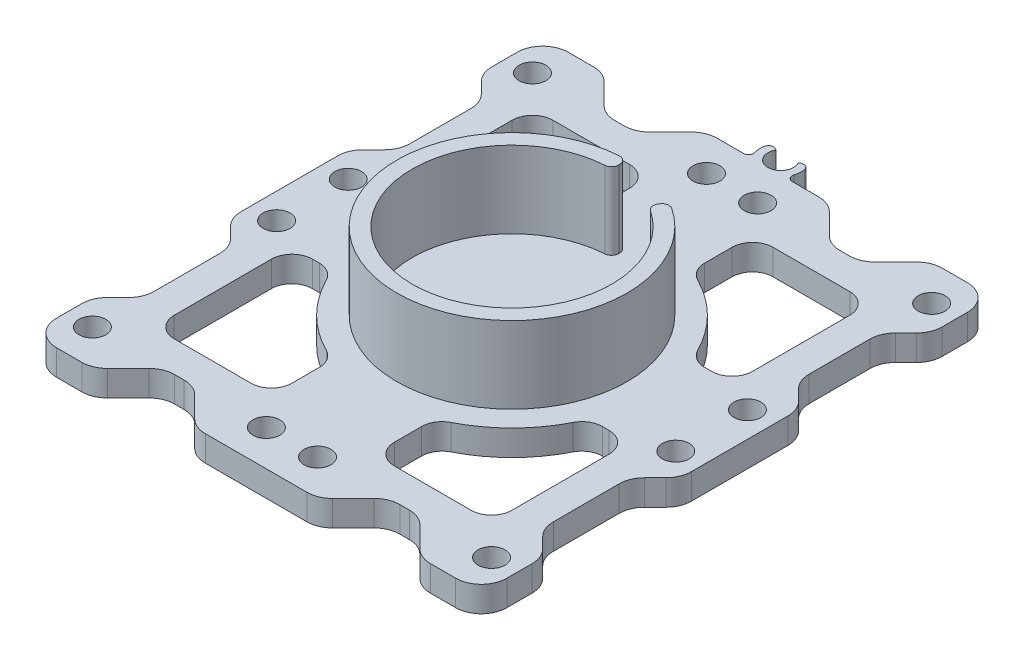
SolidWorks part; units mm, degrees
ref_plane "Front Plane" through (0, 0, 0) normal (0, 0, 1) x (1, 0, 0)
ref_plane "Top Plane" through (0, 0, 0) normal (0, 1, 0) x (1, 0, 0)
ref_plane "Right Plane" through (0, 0, 0) normal (1, 0, 0) x (0, 0, -1)
sketch "Sketch1" plane through (0, 0, 0) normal (0, 1, 0) x (1, 0, 0)
  line L1 (9.9289, 50) -> (4.7697, 50)
  line L2 (-44, 45) -> (-44, 40.0711)
  line L3 (-39, -50) -> (-34.0711, -50)
  line L5 (-30.5355, 48.5355) -> (-26.4645, 44.4645)
  line L6 (-22.9289, 43) -> (-21.0711, 43)
  line L7 (-17.5355, 44.4645) -> (-13.4645, 48.5355)
  line L8 (-42.5355, 36.5355) -> (-40.4645, 34.4645)
  line L9 (-39, 30.9289) -> (-39, 19.0711)
  line L10 (-40.4645, 15.5355) -> (-42.5355, 13.4645)
  line L11 (-42.5355, -12.4645) -> (-40.4645, -14.5355)
  line L12 (-39, -18.0711) -> (-39, -30.9289)
  line L13 (-40.4645, -34.4645) -> (-42.5355, -36.5355)
  line L14 (-30.5355, -48.5355) -> (-26.4645, -44.4645)
  line L15 (-22.9289, -43) -> (-21.0711, -43)
  line L16 (-17.5355, -44.4645) -> (-13.4645, -48.5355)
  line L17 (-34.0711, 50) -> (-39, 50)
  line L18 (-44, 9.9289) -> (-44, -8.9289)
  line L19 (-44, -40.0711) -> (-44, -45)
  line L20 (-9.9289, -50) -> (9.9289, -50)
  line L21 (0, -55) -> (0, 55) construction
  line L22 (44, -40.0711) -> (44, -45)
  line L23 (44, 9.9289) -> (44, -8.9289)
  line L24 (34.0711, 50) -> (39, 50)
  line L25 (17.5355, -44.4645) -> (13.4645, -48.5355)
  line L26 (22.9289, -43) -> (21.0711, -43)
  line L27 (30.5355, -48.5355) -> (26.4645, -44.4645)
  line L28 (40.4645, -34.4645) -> (42.5355, -36.5355)
  line L29 (39, -18.0711) -> (39, -30.9289)
  line L30 (42.5355, -12.4645) -> (40.4645, -14.5355)
  line L31 (40.4645, 15.5355) -> (42.5355, 13.4645)
  line L32 (39, 30.9289) -> (39, 19.0711)
  line L33 (42.5355, 36.5355) -> (40.4645, 34.4645)
  line L34 (17.5355, 44.4645) -> (13.4645, 48.5355)
  line L35 (22.9289, 43) -> (21.0711, 43)
  line L36 (30.5355, 48.5355) -> (26.4645, 44.4645)
  line L37 (39, -50) -> (34.0711, -50)
  line L38 (44, 45) -> (44, 40.0711)
  line L39 (-4.7697, 50) -> (-9.9289, 50)
  line L40 (2.1651, 53.75) -> (2.4495, 53.9142)
  line L42 (-2.1651, 53.75) -> (-2.4495, 53.9142)
  circle A0 centre (-39, 43) radius 2.625
  circle A1 centre (-5, 43) radius 2.625
  circle A2 centre (-39, 7) radius 2.625
  circle A3 centre (-39, -43) radius 2.625
  circle A4 centre (-5, -43) radius 2.625
  circle A5 centre (-39, -7) radius 2.625
  arc A6 (-13.4645, -48.5355) -> (-9.9289, -50) centre (-9.9289, -45) ccw
  arc A7 (-21.0711, -43) -> (-17.5355, -44.4645) centre (-21.0711, -48) cw
  arc A8 (-26.4645, -44.4645) -> (-22.9289, -43) centre (-22.9289, -48) cw
  arc A9 (-30.5355, -48.5355) -> (-34.0711, -50) centre (-34.0711, -45) cw
  arc A10 (-44, -45) -> (-39, -50) centre (-39, -45) ccw
  arc A11 (-42.5355, -36.5355) -> (-44, -40.0711) centre (-39, -40.0711) ccw
  arc A12 (-39, -30.9289) -> (-40.4645, -34.4645) centre (-44, -30.9289) cw
  arc A13 (-40.4645, -14.5355) -> (-39, -18.0711) centre (-44, -18.0711) cw
  arc A14 (-42.5355, -12.4645) -> (-44, -8.9289) centre (-39, -8.9289) cw
  arc A15 (-42.5355, 13.4645) -> (-44, 9.9289) centre (-39, 9.9289) ccw
  arc A16 (-39, 19.0711) -> (-40.4645, 15.5355) centre (-44, 19.0711) cw
  arc A17 (-40.4645, 34.4645) -> (-39, 30.9289) centre (-44, 30.9289) cw
  arc A18 (-42.5355, 36.5355) -> (-44, 40.0711) centre (-39, 40.0711) cw
  arc A19 (-13.4645, 48.5355) -> (-9.9289, 50) centre (-9.9289, 45) cw
  arc A20 (-21.0711, 43) -> (-17.5355, 44.4645) centre (-21.0711, 48) ccw
  arc A21 (-26.4645, 44.4645) -> (-22.9289, 43) centre (-22.9289, 48) ccw
  arc A22 (-30.5355, 48.5355) -> (-34.0711, 50) centre (-34.0711, 45) ccw
  arc A23 (-39, 50) -> (-44, 45) centre (-39, 45) ccw
  arc A24 (39, 50) -> (44, 45) centre (39, 45) cw
  arc A25 (30.5355, 48.5355) -> (34.0711, 50) centre (34.0711, 45) cw
  arc A26 (26.4645, 44.4645) -> (22.9289, 43) centre (22.9289, 48) cw
  arc A27 (21.0711, 43) -> (17.5355, 44.4645) centre (21.0711, 48) cw
  arc A28 (13.4645, 48.5355) -> (9.9289, 50) centre (9.9289, 45) ccw
  arc A29 (42.5355, 36.5355) -> (44, 40.0711) centre (39, 40.0711) ccw
  arc A30 (40.4645, 34.4645) -> (39, 30.9289) centre (44, 30.9289) ccw
  arc A31 (39, 19.0711) -> (40.4645, 15.5355) centre (44, 19.0711) ccw
  arc A32 (42.5355, 13.4645) -> (44, 9.9289) centre (39, 9.9289) cw
  arc A33 (42.5355, -12.4645) -> (44, -8.9289) centre (39, -8.9289) ccw
  arc A34 (40.4645, -14.5355) -> (39, -18.0711) centre (44, -18.0711) ccw
  arc A35 (39, -30.9289) -> (40.4645, -34.4645) centre (44, -30.9289) ccw
  arc A36 (42.5355, -36.5355) -> (44, -40.0711) centre (39, -40.0711) cw
  arc A37 (44, -45) -> (39, -50) centre (39, -45) cw
  arc A38 (30.5355, -48.5355) -> (34.0711, -50) centre (34.0711, -45) ccw
  arc A39 (26.4645, -44.4645) -> (22.9289, -43) centre (22.9289, -48) ccw
  arc A40 (21.0711, -43) -> (17.5355, -44.4645) centre (21.0711, -48) ccw
  arc A41 (13.4645, -48.5355) -> (9.9289, -50) centre (9.9289, -45) cw
  circle A42 centre (39, -7) radius 2.625
  circle A43 centre (5, -43) radius 2.625
  circle A44 centre (39, -43) radius 2.625
  circle A45 centre (39, 7) radius 2.625
  circle A46 centre (5, 43) radius 2.625
  circle A47 centre (39, 43) radius 2.625
  arc A48 (-2.1651, 53.75) -> (2.1651, 53.75) centre (0, 52.5) ccw
  arc A49 (3.8158, 51.3) -> (3.9327, 53.2309) centre (0, 52.5) ccw
  arc A50 (-3.9327, 53.2309) -> (-3.8158, 51.3) centre (0, 52.5) ccw
  arc A51 (2.4495, 53.9142) -> (3.9327, 53.2309) centre (2.9495, 53.0482) cw
  arc A52 (-2.4495, 53.9142) -> (-3.9327, 53.2309) centre (-2.9495, 53.0482) ccw
  arc A53 (3.8158, 51.3) -> (4.7697, 50) centre (4.7697, 51) ccw
  arc A54 (-4.7697, 50) -> (-3.8158, 51.3) centre (-4.7697, 51) ccw
  point P36 (-12, -50)
  point P43 (-32, -50)
  point P46 (-44, -50)
  point P49 (-44, -38)
  point P56 (-44, -11)
  point P59 (-44, 12)
  point P66 (-44, 38)
  point P69 (-12, 50)
  point P76 (-32, 50)
  point P79 (-44, 50)
  point P148 (44, 50)
  point P149 (32, 50)
  point P150 (12, 50)
  point P151 (44, 38)
  point P152 (44, 12)
  point P153 (44, -11)
  point P154 (44, -38)
  point P155 (44, -50)
  point P156 (32, -50)
  point P157 (12, -50)
  point P166 (-3.4641, 54.5)
  point P171 (-3.1225, 50)
  dimension "D4" = 5.25
  dimension "D5" = 5.25
  dimension "D6" = 5.25
  dimension "D7" = 5.25
  dimension "D8" = 5.25
  dimension "D9" = 5.25
  dimension "D36" = 5
  dimension "D18" = 5
  dimension "D24" = 8
  dimension "D38" = 1
  dimension "D2" = 100
  dimension "D10" = 5
  dimension "D11" = 5
  dimension "D12" = 5
  dimension "D13" = 5
  dimension "D14" = 7
  dimension "D15" = 43
  dimension "D16" = 43
  dimension "D17" = 7
  dimension "D19" = 2.5
  dimension "D20" = 7
  dimension "D21" = 7
  dimension "D22" = 12
  dimension "D23" = 12
  dimension "D25" = 135
  dimension "D26" = 135
  dimension "D27" = 38
  dimension "D28" = 135
  dimension "D29" = 39
  dimension "D30" = 12
  dimension "D31" = 135
  dimension "D32" = 12
  dimension "D33" = 30
  dimension "D34" = 135
  dimension "D35" = 135
  dimension "D37" = 30
extrude "Boss-Extrude1" add sketch "Sketch1" along normal blind 5
sketch "Sketch2" plane through (0, 5, 0) normal (0, 1, 0) x (1, 0, 0)
  line L1 (0, 20.8531) -> (0, 21.0535)
  line L3 (10.4265, 18.0593) -> (10.5268, 18.2329)
  line L4 (-39, 30.9289) -> (-39, 19.0711) construction
  line L7 (39, 19.0711) -> (39, 30.9289) construction
  arc A0 (-1.3062, 19.4562) -> (10.8593, 16.1965) centre (0, 0) ccw
  arc A1 (-1.4929, 22.4504) -> (12.5181, 18.6962) centre (0, 0) ccw
  arc A2 (10.5268, 18.2329) -> (12.5181, 18.6962) centre (11.7392, 17.5329) cw
  arc A3 (10.8593, 16.1965) -> (10.4265, 18.0593) centre (11.639, 17.3593) cw
  arc A4 (0, 21.0535) -> (-1.4929, 22.4504) centre (-1.4, 21.0535) ccw
  arc A5 (-1.3062, 19.4562) -> (0, 20.8531) centre (-1.4, 20.8531) ccw
  dimension "D1" = 39
  dimension "D2" = 45
  dimension "D5" = 1.4
  dimension "D3" = 0
  dimension "D4" = 30
extrude "Boss-Extrude2" add sketch "Sketch2" along normal blind 15
sketch "Sketch3" plane through (0, 5, 0) normal (0, 1, 0) x (1, 0, 0)
  line L0 (-29, 37) -> (-14, 37)
  line L1 (-10, 33) -> (-10, 27.6586)
  line L2 (-33, 33) -> (-33, 14)
  line L3 (-29, 10) -> (-27.6586, 10)
  line L4 (-39, 30.9289) -> (-39, 19.0711) construction
  line L5 (-21.0711, 43) -> (-22.9289, 43) construction
  line L6 (0, -2.75) -> (0, 2.75) construction
  line L7 (33, 33) -> (33, 14)
  line L8 (29, 37) -> (14, 37)
  line L9 (10, 33) -> (10, 27.6586)
  line L10 (29, 10) -> (27.6586, 10)
  line L11 (-2.75, 0) -> (2.75, 0) construction
  line L12 (29, -37) -> (14, -37)
  line L13 (10, -33) -> (10, -27.6586)
  line L14 (29, -10) -> (27.6586, -10)
  line L15 (33, -33) -> (33, -14)
  line L16 (-33, -33) -> (-33, -14)
  line L17 (-29, -37) -> (-14, -37)
  line L18 (-10, -33) -> (-10, -27.6586)
  line L19 (-29, -10) -> (-27.6586, -10)
  arc A0 (-12.1935, 24.0898) -> (-24.0898, 12.1935) centre (0, 0) ccw
  arc A1 (12.1935, 24.0898) -> (24.0898, 12.1935) centre (0, 0) cw
  arc A2 (12.1935, -24.0898) -> (24.0898, -12.1935) centre (0, 0) ccw
  arc A3 (-12.1935, -24.0898) -> (-24.0898, -12.1935) centre (0, 0) cw
  arc A4 (33, 14) -> (29, 10) centre (29, 14) cw
  arc A5 (33, 33) -> (29, 37) centre (29, 33) ccw
  arc A6 (14, 37) -> (10, 33) centre (14, 33) ccw
  arc A7 (10, 27.6586) -> (12.1935, 24.0898) centre (14, 27.6586) ccw
  arc A8 (24.0898, 12.1935) -> (27.6586, 10) centre (27.6586, 14) ccw
  arc A9 (29, -37) -> (33, -33) centre (29, -33) ccw
  arc A10 (29, -10) -> (33, -14) centre (29, -14) cw
  arc A11 (24.0898, -12.1935) -> (27.6586, -10) centre (27.6586, -14) cw
  arc A12 (10, -27.6586) -> (12.1935, -24.0898) centre (14, -27.6586) cw
  arc A13 (14, -37) -> (10, -33) centre (14, -33) cw
  arc A14 (-33, -33) -> (-29, -37) centre (-29, -33) ccw
  arc A15 (-14, -37) -> (-10, -33) centre (-14, -33) ccw
  arc A16 (-10, -27.6586) -> (-12.1935, -24.0898) centre (-14, -27.6586) ccw
  arc A17 (-24.0898, -12.1935) -> (-27.6586, -10) centre (-27.6586, -14) ccw
  arc A18 (-33, -14) -> (-29, -10) centre (-29, -14) cw
  arc A19 (-29, 37) -> (-33, 33) centre (-29, 33) ccw
  arc A20 (-14, 37) -> (-10, 33) centre (-14, 33) cw
  arc A21 (-10, 27.6586) -> (-12.1935, 24.0898) centre (-14, 27.6586) cw
  arc A22 (-24.0898, 12.1935) -> (-27.6586, 10) centre (-27.6586, 14) cw
  arc A23 (-33, 14) -> (-29, 10) centre (-29, 14) ccw
  point P11 (-10, 30.3293)
  point P33 (33, 10)
  point P36 (33, 37)
  point P39 (10, 37)
  point P42 (10, 25.0799)
  point P45 (25.0799, 10)
  point P48 (33, -37)
  point P51 (33, -10)
  point P54 (25.0799, -10)
  point P57 (10, -25.0799)
  point P60 (10, -37)
  point P63 (-33, -37)
  point P66 (-10, -37)
  point P69 (-10, -25.0799)
  point P72 (-25.0799, -10)
  point P75 (-33, -10)
  point P78 (-33, 37)
  point P81 (-10, 37)
  point P84 (-10, 25.0799)
  point P87 (-25.0799, 10)
  point P90 (-33, 10)
  dimension "D5" = 27
  dimension "D6" = 4
  dimension "D1" = 6
  dimension "D2" = 6
  dimension "D3" = 10
  dimension "D4" = 10
extrude "Cut-Extrude1" cut sketch "Sketch3" against normal through all
